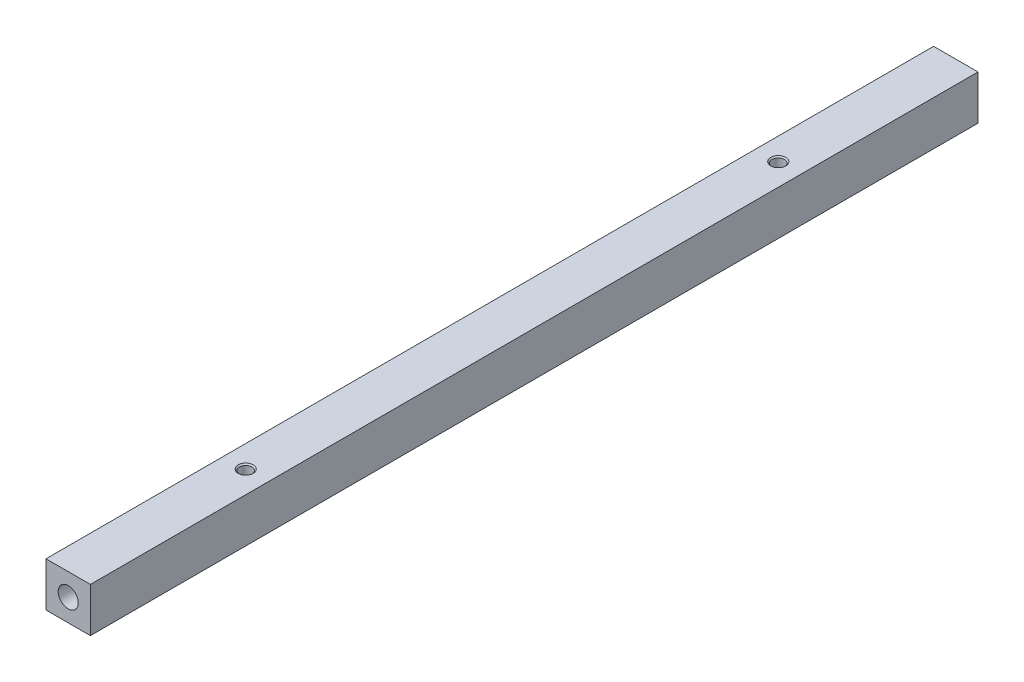
SolidWorks part; units mm, degrees
ref_plane "Ön Düzlem" through (0, 0, 0) normal (0, 0, 1) x (1, 0, 0)
ref_plane "Üst Düzlem" through (0, 0, 0) normal (0, 1, 0) x (1, 0, 0)
ref_plane "Sağ Düzlem" through (0, 0, 0) normal (1, 0, 0) x (0, 0, -1)
sketch "Çizim1" plane through (0, 0, 0) normal (0, 0, 1) x (1, 0, 0)
  line L1 (-7.5, -7.5) -> (7.5, -7.5)
  line L2 (-7.5, -7.5) -> (-7.5, 7.5)
  line L3 (-7.5, 7.5) -> (7.5, 7.5)
  line L4 (7.5, -7.5) -> (7.5, 7.5)
  line L5 (-7.5, -7.5) -> (7.5, 7.5) construction
  line L6 (-7.5, 7.5) -> (7.5, -7.5) construction
  point P0 (0, 0)
  dimension "D1" = 15
extrude "Yükseklik-Ekstrüzyon1" add sketch "Çizim1" along normal mid plane 300
hole_wizard "M8 Dişli Delik1" positions "Çizim2" profile "Çizim3" tap size "M8" standard "ISO"
sketch "Çizim2" plane through (0, 0, 150) normal (0, 0, 1) x (1, 0, 0)
  point P0 (0, 0)
sketch "Çizim3" plane through (0, 0, 150) normal (1, 0, 0) x (0, -1, 0)
  line L0 (0, 0) -> (0, 24.2929)
  line L1 (0, 24.2929) -> (3.4, 22.25)
  line L2 (3.4, 22.25) -> (3.4, 0)
  line L5 (3.4, 0) -> (0, 0)
  line L10 (0, 24.2929) -> (-3.4, 22.25) construction
  line L11 (0, -6.35) -> (0, 107.95) construction
  dimension "Tap Drill Dia." = 6.8
  dimension "Tap Drill Depth" = 22.25
  dimension "Drill Angle" = 118
cosmetic thread "Delik Dişi1" parameters "D1"=16, "D2"=8
mirror "Aynalama1" about plane through (0, 0, 0) normal (0, 0, 1) of "M8 Dişli Delik1"
cosmetic thread "Delik Dişi2" parameters "D1"=16, "D2"=8
hole_wizard "M5 Dişli Delik1" positions "Çizim4" profile "Çizim5" tap size "M5" standard "ISO" end condition through all
sketch "Çizim4" plane through (0, 7.5, 0) normal (0, 1, 0) x (1, 0, 0)
  point P0 (0, 90)
  point P6 (0, 0)
  dimension "D1" = 90
sketch "Çizim5" plane through (0, 7.5, -90) normal (1, 0, 0) x (0, 0, 1)
  line L0 (0, 0) -> (0, 15)
  line L1 (0, 15) -> (2.1, 15)
  line L2 (2.1, 15) -> (2.1, 0.425)
  line L3 (2.1, 0.425) -> (2.525, 0)
  line L5 (2.525, 0) -> (0, 0)
  line L6 (-2.1, 0.425) -> (-2.525, 0) construction
  line L11 (0, -6.35) -> (0, 107.95) construction
  dimension "Thru Tap Drill Dia." = 4.2
  dimension "Thru Tap Drill Depth" = 15
  dimension "Near C'Sink Dia." = 5.05
  dimension "Near C'Sink Angle" = 90
cosmetic thread "Delik Dişi3" parameters "D2"=5
mirror "Aynalama2" about plane through (0, 0, 0) normal (0, 0, 1) of "M5 Dişli Delik1"
cosmetic thread "Delik Dişi4" parameters "D2"=5
